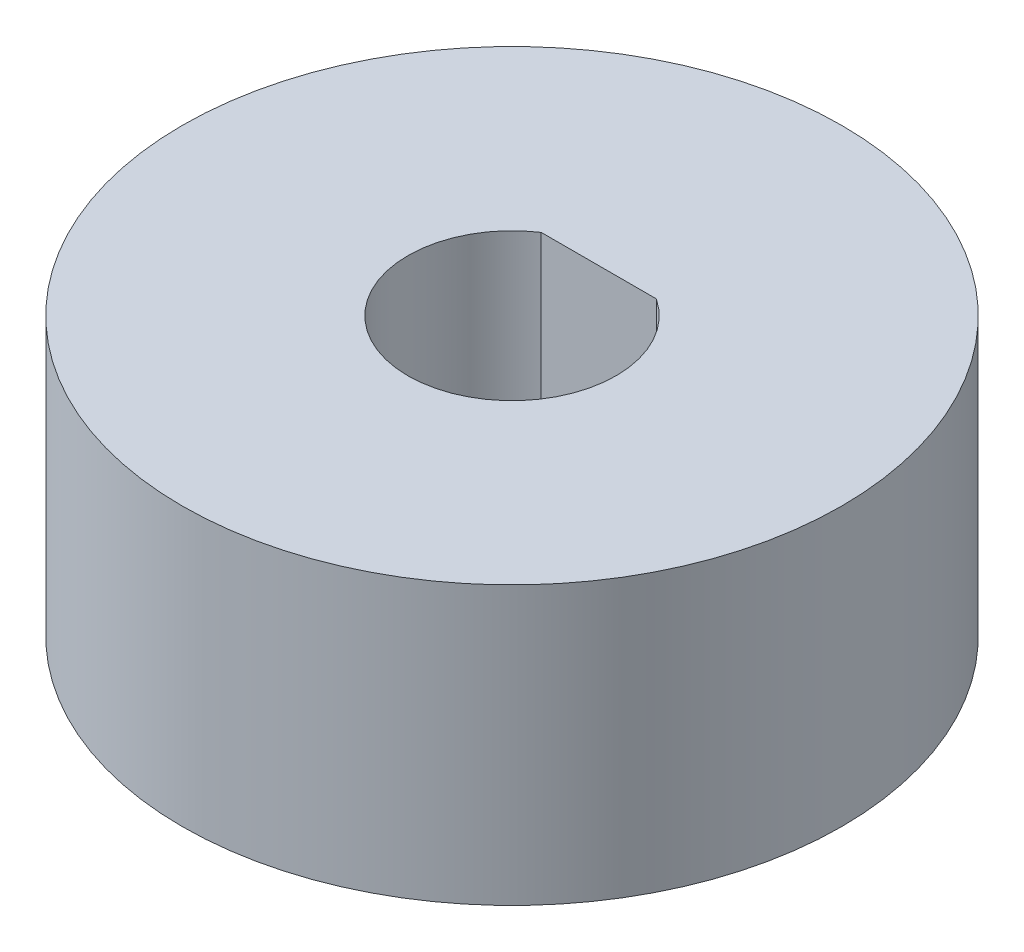
SolidWorks part; units mm, degrees
ref_plane "前视基准面" through (0, 0, 0) normal (0, 0, 1) x (1, 0, 0)
ref_plane "上视基准面" through (0, 0, 0) normal (0, 1, 0) x (1, 0, 0)
ref_plane "右视基准面" through (0, 0, 0) normal (1, 0, 0) x (0, 0, -1)
sketch "草图1" plane through (0, 0, 0) normal (0, 0, 1) x (1, 0, 0)
  line L0 (-3, 0) -> (-9.5, 0)
  line L1 (-3, 0) -> (-3, 8)
  line L2 (0, 0) -> (0, 12.2296) construction
  line L5 (-3, 8) -> (-9.5, 8)
  line L6 (-9.5, 8) -> (-9.5, 0)
  dimension "D1" = 3
  dimension "D2" = 9.5
  dimension "D3" = 8
revolve "旋转1" add sketch "草图1" angle 360 about L2
sketch "草图2" plane through (0, 0, 0) normal (0, -1, 0) x (1, 0, 0)
  line L0 (-1.6583, -2.5) -> (1.6583, -2.5)
  circle A0 centre (0, 0) radius 3
  circle A1 centre (0, 0) radius 3 construction
  circle M3 centre (0, 0) radius 3
  dimension "D1" = 2.5
extrude "凸台-拉伸1" add sketch "草图2" against normal up to surface (8 mm away) contours L0 M3
